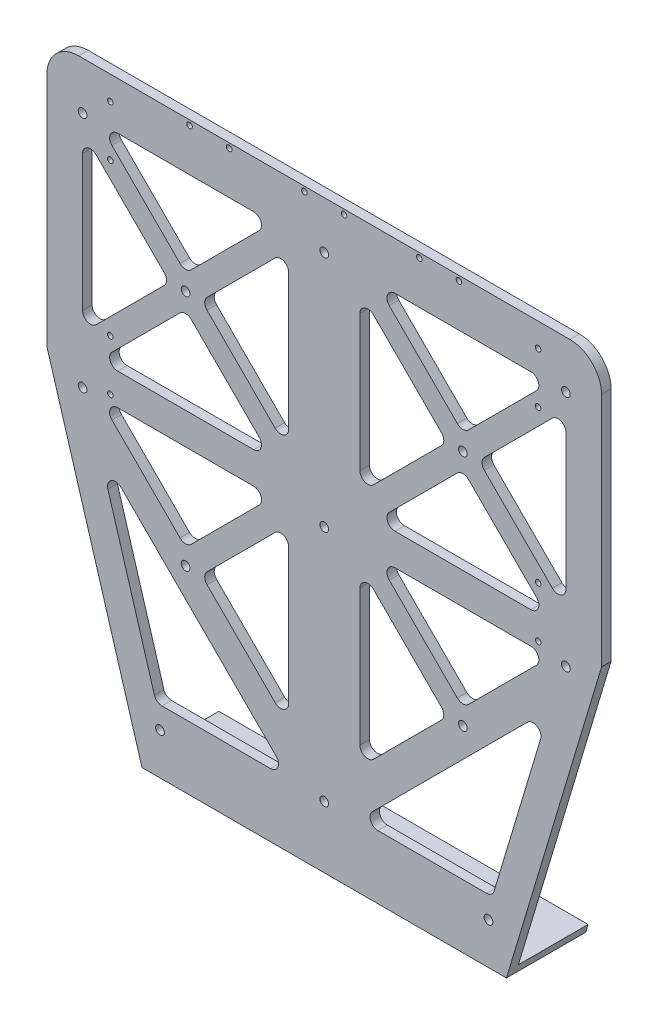
SolidWorks part; units mm, degrees
material "6061 合金"
ref_plane "前视基准面" through (0, 0, 0) normal (0, 0, 1) x (1, 0, 0)
ref_plane "上视基准面" through (0, 0, 0) normal (0, 1, 0) x (1, 0, 0)
ref_plane "右视基准面" through (0, 0, 0) normal (1, 0, 0) x (0, 0, -1)
other "Configuration Table"
sketch "草图1" plane through (0, 0, 0) normal (0, 1, 0) x (1, 0, 0)
  line L0 (0, 55.3951) -> (0, -55.5471) construction
  line L1 (-216.8213, 25) -> (288.5349, 25) construction
  line L2 (-175, 50) -> (175, 50)
  line L3 (-175, 50) -> (-175, 0)
  line L4 (-175, 0) -> (175, 0)
  line L5 (175, 50) -> (175, 0)
  line L6 (10, 25) -> (90, 25) construction
  circle A0 centre (130, 25) radius 2.75
  circle A1 centre (50, 25) radius 2.75
  circle A2 centre (-130, 25) radius 2.75
  circle A3 centre (-50, 25) radius 2.75
  circle A4 centre (10, 25) radius 2.75
  circle A5 centre (90, 25) radius 2.75
  circle A6 centre (-90, 25) radius 2.75
  circle A7 centre (-10, 25) radius 2.75
  dimension "D3" = 5.5
  dimension "D6" = 40
  dimension "D1" = 50
  dimension "D2" = 350
  dimension "D4" = 80
  dimension "D5" = 50
  dimension "D8" = 80
  dimension "D7" = 2
extrude "凸台-拉伸1" add sketch "草图1" along normal blind 5
sketch "草图2" plane through (0, 5, 0) normal (0, 1, 0) x (1, 0, 0)
  line L0 (-175, 50) -> (-175, 0) construction
  line L1 (-175, 6) -> (175, 6)
  line L2 (-175, 6) -> (-175, 0)
  line L3 (-175, 0) -> (175, 0)
  line L4 (175, 6) -> (175, 0)
  dimension "D1" = 6
extrude "凸台-拉伸2" add sketch "草图2" along normal blind 364
sketch "草图3" plane through (0, 0, -6) normal (0, 0, -1) x (-1, 0, 0)
  line L0 (83.9645, 137.5355) -> (41.0355, 180.4645)
  line L1 (0, 0) -> (0, 572.5398) construction
  line L2 (44.5711, 189) -> (130.4289, 189)
  line L15 (133.9645, 180.4645) -> (91.0355, 137.5355)
  line L28 (44.5711, 339) -> (130.4289, 339)
  line L29 (133.9645, 330.4645) -> (91.0355, 287.5355)
  line L30 (83.9645, 287.5355) -> (41.0355, 330.4645)
  line L31 (-175, 369) -> (175, 369) construction
  line L32 (87.5, 645.5729) -> (87.5, -148.8574) construction
  line L33 (73.9645, 120.4645) -> (31.0355, 77.5355)
  line L34 (175, 369) -> (175, 5) construction
  line L35 (101.0355, 277.5355) -> (143.9645, 320.4645)
  line L36 (152.5, 316.9289) -> (152.5, 231.0711)
  line L37 (143.9645, 227.5355) -> (101.0355, 270.4645)
  line L38 (91.0355, 260.4645) -> (133.9645, 217.5355)
  line L39 (130.4289, 209) -> (44.5711, 209)
  line L40 (41.0355, 217.5355) -> (83.9645, 260.4645)
  line L41 (73.9645, 270.4645) -> (31.0355, 227.5355)
  line L42 (22.5, 231.0711) -> (22.5, 316.9289)
  line L43 (31.0355, 320.4645) -> (73.9645, 277.5355)
  line L104 (22.5, 81.0711) -> (22.5, 166.9289)
  line L105 (31.0355, 170.4645) -> (73.9645, 127.5355)
  line L106 (101.0355, 127.5355) -> (143.9645, 170.4645) construction
  line L107 (152.5, 166.9289) -> (152.5, 81.0711) construction
  line L108 (143.9645, 77.5355) -> (101.0355, 120.4645) construction
  line L109 (91.0355, 110.4645) -> (133.9645, 67.5355) construction
  line L110 (130.4289, 59) -> (44.5711, 59) construction
  line L111 (41.0355, 67.5355) -> (83.9645, 110.4645) construction
  line L124 (-91.0355, 137.5355) -> (-133.9645, 180.4645)
  line L125 (-130.4289, 189) -> (-44.5711, 189)
  line L126 (-41.0355, 180.4645) -> (-83.9645, 137.5355)
  line L127 (-101.0355, 120.4645) -> (-143.9645, 77.5355) construction
  line L128 (-152.5, 81.0711) -> (-152.5, 166.9289) construction
  line L129 (-143.9645, 170.4645) -> (-101.0355, 127.5355) construction
  line L130 (-73.9645, 127.5355) -> (-31.0355, 170.4645)
  line L131 (-22.5, 166.9289) -> (-22.5, 81.0711)
  line L132 (-31.0355, 77.5355) -> (-73.9645, 120.4645)
  line L133 (-83.9645, 110.4645) -> (-41.0355, 67.5355) construction
  line L134 (-44.5711, 59) -> (-130.4289, 59) construction
  line L135 (-133.9645, 67.5355) -> (-91.0355, 110.4645) construction
  line L148 (-91.0355, 287.5355) -> (-133.9645, 330.4645)
  line L149 (-130.4289, 339) -> (-44.5711, 339)
  line L150 (-41.0355, 330.4645) -> (-83.9645, 287.5355)
  line L151 (-101.0355, 270.4645) -> (-143.9645, 227.5355)
  line L152 (-152.5, 231.0711) -> (-152.5, 316.9289)
  line L153 (-143.9645, 320.4645) -> (-101.0355, 277.5355)
  line L154 (-73.9645, 277.5355) -> (-31.0355, 320.4645)
  line L155 (-22.5, 316.9289) -> (-22.5, 231.0711)
  line L156 (-31.0355, 227.5355) -> (-73.9645, 270.4645)
  line L157 (-83.9645, 260.4645) -> (-41.0355, 217.5355)
  line L158 (-44.5711, 209) -> (-130.4289, 209)
  line L159 (-133.9645, 217.5355) -> (-91.0355, 260.4645)
  line L160 (83.9645, -12.4645) -> (41.0355, 30.4645) [skipped]
  line L161 (133.9645, 30.4645) -> (91.0355, -12.4645) [skipped]
  line L162 (73.9645, -29.5355) -> (31.0355, -72.4645) [skipped]
  line L163 (22.5, -68.9289) -> (22.5, 16.9289) [skipped]
  line L164 (31.0355, 20.4645) -> (73.9645, -22.4645) [skipped]
  line L165 (101.0355, -22.4645) -> (143.9645, 20.4645) [skipped]
  line L166 (152.5, 16.9289) -> (152.5, -68.9289) [skipped]
  line L167 (143.9645, -72.4645) -> (101.0355, -29.5355) [skipped]
  line L168 (91.0355, -39.5355) -> (133.9645, -82.4645) [skipped]
  line L169 (130.4289, -91) -> (44.5711, -91) [skipped]
  line L170 (41.0355, -82.4645) -> (83.9645, -39.5355) [skipped]
  line L171 (-91.0355, -12.4645) -> (-133.9645, 30.4645) [skipped]
  line L172 (-41.0355, 30.4645) -> (-83.9645, -12.4645) [skipped]
  line L173 (-101.0355, -29.5355) -> (-143.9645, -72.4645) [skipped]
  line L174 (-152.5, -68.9289) -> (-152.5, 16.9289) [skipped]
  line L175 (-143.9645, 20.4645) -> (-101.0355, -22.4645) [skipped]
  line L176 (-73.9645, -22.4645) -> (-31.0355, 20.4645) [skipped]
  line L177 (-22.5, 16.9289) -> (-22.5, -68.9289) [skipped]
  line L178 (-31.0355, -72.4645) -> (-73.9645, -29.5355) [skipped]
  line L179 (-83.9645, -39.5355) -> (-41.0355, -82.4645) [skipped]
  line L180 (-44.5711, -91) -> (-130.4289, -91) [skipped]
  line L181 (-133.9645, -82.4645) -> (-91.0355, -39.5355) [skipped]
  line L182 (44.5711, 39) -> (130.4289, 39) [skipped]
  line L183 (-130.4289, 39) -> (-44.5711, 39) [skipped]
  arc A0 (22.5, 316.9289) -> (31.0355, 320.4645) centre (27.5, 316.9289) cw
  arc A1 (31.0355, 227.5355) -> (22.5, 231.0711) centre (27.5, 231.0711) cw
  arc A2 (73.9645, 270.4645) -> (73.9645, 277.5355) centre (70.4289, 274) ccw
  arc A3 (44.5711, 209) -> (41.0355, 217.5355) centre (44.5711, 214) cw
  arc A4 (130.4289, 209) -> (133.9645, 217.5355) centre (130.4289, 214) ccw
  arc A5 (91.0355, 260.4645) -> (83.9645, 260.4645) centre (87.5, 256.9289) ccw
  arc A6 (101.0355, 270.4645) -> (101.0355, 277.5355) centre (104.5711, 274) cw
  arc A7 (143.9645, 227.5355) -> (152.5, 231.0711) centre (147.5, 231.0711) ccw
  arc A8 (152.5, 316.9289) -> (143.9645, 320.4645) centre (147.5, 316.9289) ccw
  arc A9 (91.0355, 287.5355) -> (83.9645, 287.5355) centre (87.5, 291.0711) cw
  arc A10 (133.9645, 330.4645) -> (130.4289, 339) centre (130.4289, 334) ccw
  arc A11 (41.0355, 330.4645) -> (44.5711, 339) centre (44.5711, 334) cw
  arc A12 (41.0355, 180.4645) -> (44.5711, 189) centre (44.5711, 184) cw
  arc A13 (91.0355, 137.5355) -> (83.9645, 137.5355) centre (87.5, 141.0711) cw
  arc A14 (133.9645, 180.4645) -> (130.4289, 189) centre (130.4289, 184) ccw
  arc A15 (73.9645, 120.4645) -> (73.9645, 127.5355) centre (70.4289, 124) ccw
  arc A16 (31.0355, 77.5355) -> (22.5, 81.0711) centre (27.5, 81.0711) cw
  arc A17 (22.5, 166.9289) -> (31.0355, 170.4645) centre (27.5, 166.9289) cw
  arc A18 (152.5, 166.9289) -> (143.9645, 170.4645) centre (147.5, 166.9289) ccw construction
  arc A19 (101.0355, 120.4645) -> (101.0355, 127.5355) centre (104.5711, 124) cw construction
  arc A20 (143.9645, 77.5355) -> (152.5, 81.0711) centre (147.5, 81.0711) ccw construction
  arc A21 (91.0355, 110.4645) -> (83.9645, 110.4645) centre (87.5, 106.9289) ccw construction
  arc A22 (130.4289, 59) -> (133.9645, 67.5355) centre (130.4289, 64) ccw construction
  arc A23 (44.5711, 59) -> (41.0355, 67.5355) centre (44.5711, 64) cw construction
  arc A36 (-133.9645, 180.4645) -> (-130.4289, 189) centre (-130.4289, 184) cw
  arc A37 (-83.9645, 137.5355) -> (-91.0355, 137.5355) centre (-87.5, 141.0711) cw
  arc A38 (-41.0355, 180.4645) -> (-44.5711, 189) centre (-44.5711, 184) ccw
  arc A39 (-101.0355, 120.4645) -> (-101.0355, 127.5355) centre (-104.5711, 124) ccw construction
  arc A40 (-143.9645, 77.5355) -> (-152.5, 81.0711) centre (-147.5, 81.0711) cw construction
  arc A41 (-152.5, 166.9289) -> (-143.9645, 170.4645) centre (-147.5, 166.9289) cw construction
  arc A42 (-22.5, 166.9289) -> (-31.0355, 170.4645) centre (-27.5, 166.9289) ccw
  arc A43 (-73.9645, 120.4645) -> (-73.9645, 127.5355) centre (-70.4289, 124) cw
  arc A44 (-31.0355, 77.5355) -> (-22.5, 81.0711) centre (-27.5, 81.0711) ccw
  arc A45 (-83.9645, 110.4645) -> (-91.0355, 110.4645) centre (-87.5, 106.9289) ccw construction
  arc A46 (-44.5711, 59) -> (-41.0355, 67.5355) centre (-44.5711, 64) ccw construction
  arc A47 (-130.4289, 59) -> (-133.9645, 67.5355) centre (-130.4289, 64) cw construction
  arc A60 (-133.9645, 330.4645) -> (-130.4289, 339) centre (-130.4289, 334) cw
  arc A61 (-83.9645, 287.5355) -> (-91.0355, 287.5355) centre (-87.5, 291.0711) cw
  arc A62 (-41.0355, 330.4645) -> (-44.5711, 339) centre (-44.5711, 334) ccw
  arc A63 (-101.0355, 270.4645) -> (-101.0355, 277.5355) centre (-104.5711, 274) ccw
  arc A64 (-143.9645, 227.5355) -> (-152.5, 231.0711) centre (-147.5, 231.0711) cw
  arc A65 (-152.5, 316.9289) -> (-143.9645, 320.4645) centre (-147.5, 316.9289) cw
  arc A66 (-22.5, 316.9289) -> (-31.0355, 320.4645) centre (-27.5, 316.9289) ccw
  arc A67 (-73.9645, 270.4645) -> (-73.9645, 277.5355) centre (-70.4289, 274) cw
  arc A68 (-31.0355, 227.5355) -> (-22.5, 231.0711) centre (-27.5, 231.0711) ccw
  arc A69 (-83.9645, 260.4645) -> (-91.0355, 260.4645) centre (-87.5, 256.9289) ccw
  arc A70 (-44.5711, 209) -> (-41.0355, 217.5355) centre (-44.5711, 214) ccw
  arc A71 (-130.4289, 209) -> (-133.9645, 217.5355) centre (-130.4289, 214) cw
  circle A72 centre (87.5, 274) radius 2.75
  circle A73 centre (87.5, 124) radius 2.75
  circle A75 centre (-87.5, 124) radius 2.75
  circle A77 centre (-87.5, 274) radius 2.75
  circle A78 centre (152.5, 339) radius 2.75
  circle A79 centre (152.5, 189) radius 2.75
  circle A80 centre (152.5, 39) radius 2.75
  circle A81 centre (-152.5, 39) radius 2.75
  circle A82 centre (-152.5, 189) radius 2.75
  circle A83 centre (-152.5, 339) radius 2.75
  circle A84 centre (0, 339) radius 2.75
  circle A85 centre (0, 189) radius 2.75
  circle A86 centre (0, 39) radius 2.75
  arc A87 (91.0355, -12.4645) -> (83.9645, -12.4645) centre (87.5, -8.9289) cw [skipped]
  arc A88 (73.9645, -29.5355) -> (73.9645, -22.4645) centre (70.4289, -26) ccw [skipped]
  arc A89 (31.0355, -72.4645) -> (22.5, -68.9289) centre (27.5, -68.9289) cw [skipped]
  arc A90 (22.5, 16.9289) -> (31.0355, 20.4645) centre (27.5, 16.9289) cw [skipped]
  arc A91 (152.5, 16.9289) -> (143.9645, 20.4645) centre (147.5, 16.9289) ccw [skipped]
  arc A92 (101.0355, -29.5355) -> (101.0355, -22.4645) centre (104.5711, -26) cw [skipped]
  arc A93 (143.9645, -72.4645) -> (152.5, -68.9289) centre (147.5, -68.9289) ccw [skipped]
  arc A94 (91.0355, -39.5355) -> (83.9645, -39.5355) centre (87.5, -43.0711) ccw [skipped]
  arc A95 (130.4289, -91) -> (133.9645, -82.4645) centre (130.4289, -86) ccw [skipped]
  arc A96 (44.5711, -91) -> (41.0355, -82.4645) centre (44.5711, -86) cw [skipped]
  arc A97 (-83.9645, -12.4645) -> (-91.0355, -12.4645) centre (-87.5, -8.9289) cw [skipped]
  arc A98 (-101.0355, -29.5355) -> (-101.0355, -22.4645) centre (-104.5711, -26) ccw [skipped]
  arc A99 (-143.9645, -72.4645) -> (-152.5, -68.9289) centre (-147.5, -68.9289) cw [skipped]
  arc A100 (-152.5, 16.9289) -> (-143.9645, 20.4645) centre (-147.5, 16.9289) cw [skipped]
  arc A101 (-22.5, 16.9289) -> (-31.0355, 20.4645) centre (-27.5, 16.9289) ccw [skipped]
  arc A102 (-73.9645, -29.5355) -> (-73.9645, -22.4645) centre (-70.4289, -26) cw [skipped]
  arc A103 (-31.0355, -72.4645) -> (-22.5, -68.9289) centre (-27.5, -68.9289) ccw [skipped]
  arc A104 (-83.9645, -39.5355) -> (-91.0355, -39.5355) centre (-87.5, -43.0711) ccw [skipped]
  arc A105 (-44.5711, -91) -> (-41.0355, -82.4645) centre (-44.5711, -86) ccw [skipped]
  arc A106 (-130.4289, -91) -> (-133.9645, -82.4645) centre (-130.4289, -86) cw [skipped]
  circle A107 centre (87.5, -26) radius 2.75 [skipped]
  circle A108 centre (-87.5, -26) radius 2.75 [skipped]
  arc A109 (133.9645, 30.4645) -> (130.4289, 39) centre (130.4289, 34) ccw [skipped]
  arc A110 (41.0355, 30.4645) -> (44.5711, 39) centre (44.5711, 34) cw [skipped]
  arc A111 (-41.0355, 30.4645) -> (-44.5711, 39) centre (-44.5711, 34) ccw [skipped]
  arc A112 (-133.9645, 30.4645) -> (-130.4289, 39) centre (-130.4289, 34) cw [skipped]
  point P12 (87.5, 274)
  point P25 (87.5, 274)
  point P43 (87.5, 284)
  point P46 (142.5, 339)
  point P49 (32.5, 339)
  dimension "D7" = 5
  dimension "D12" = 5.5
  dimension "D17" = 5.5
  dimension "D20" = 5.5
  dimension "D1" = 45
  dimension "D2" = 45
  dimension "D3" = 110
  dimension "D4" = 30
  dimension "D5" = 10
  dimension "D6" = 4
  dimension "D8" = 3
  dimension "D9" = 2
  dimension "D10" = 20
  dimension "D11" = 45
  dimension "D15" = 150
  dimension "D16" = 175
  dimension "D18" = 3
  dimension "D19" = 150
  dimension "D13" = 3
  dimension "D14" = 2
  dimension "D21" = 3
extrude "切除-拉伸1" cut sketch "草图3" against normal blind 500
sketch "草图4" plane through (0, 0, 0) normal (0, 0, 1) x (1, 0, 0)
  line L0 (0, 0) -> (0, 524.5854) construction
  line L1 (-175, 0) -> (175, 0) construction
  line L2 (-175, 369) -> (175, 369) construction
  circle A0 centre (60, 366) radius 1.75
  circle A1 centre (85, 366) radius 1.75
  circle A2 centre (12.5, 366) radius 1.75
  circle A3 centre (-12.5, 366) radius 1.75
  circle A4 centre (-85, 366) radius 1.75
  circle A5 centre (-60, 366) radius 1.75
  dimension "D1" = 3.5
  dimension "D2" = 3
  dimension "D3" = 60
  dimension "D4" = 25
  dimension "D5" = 12.5
extrude "切除-拉伸2" cut sketch "草图4" against normal blind 10
fillet "圆角1" radius 20 2 edges at (-175, 369, -3) (175, 369, -3)
sketch "草图5" plane through (0, 0, -6) normal (0, 0, -1) x (-1, 0, 0)
  line L0 (0, 431.6761) -> (0, -91.3276) construction
  line L1 (172, 381.63) -> (172, -6.2467) construction
  line L2 (175, 349) -> (175, 5) construction
  line L3 (142.7928, 280) -> (227.4318, 280) construction
  line L4 (-175, 5) -> (175, 5) construction
  line L5 (164.8, 155.6) -> (170, 155.6)
  line L6 (164.8, 155.6) -> (164.8, 130.4)
  line L7 (164.8, 130.4) -> (170, 130.4)
  line L8 (170, 155.6) -> (170, 130.4)
  line L9 (164.8, 110.4) -> (170, 110.4)
  line L10 (164.8, 110.4) -> (164.8, 85.2)
  line L11 (164.8, 85.2) -> (170, 85.2)
  line L12 (170, 110.4) -> (170, 85.2)
  line L13 (164.8, 65.2) -> (170, 65.2)
  line L14 (164.8, 65.2) -> (164.8, 40)
  line L15 (164.8, 40) -> (170, 40)
  line L16 (170, 65.2) -> (170, 40)
  line L17 (-142.7928, 280) -> (-227.4318, 280) construction
  line L18 (-172, 381.63) -> (-172, -6.2467) construction
  line L19 (-170, 65.2) -> (-170, 40)
  line L20 (-164.8, 40) -> (-170, 40)
  line L21 (-164.8, 65.2) -> (-164.8, 40)
  line L22 (-164.8, 65.2) -> (-170, 65.2)
  line L23 (-170, 110.4) -> (-170, 85.2)
  line L24 (-164.8, 85.2) -> (-170, 85.2)
  line L25 (-164.8, 110.4) -> (-164.8, 85.2)
  line L26 (-164.8, 110.4) -> (-170, 110.4)
  line L27 (-170, 155.6) -> (-170, 130.4)
  line L28 (-164.8, 130.4) -> (-170, 130.4)
  line L29 (-164.8, 155.6) -> (-164.8, 130.4)
  line L30 (-164.8, 155.6) -> (-170, 155.6)
  circle A0 centre (172, 330) radius 1.75
  circle A1 centre (172, 230) radius 1.75
  circle A2 centre (-172, 230) radius 1.75
  circle A3 centre (-172, 330) radius 1.75
  dimension "D2" = 3.5
  dimension "D1" = 3
  dimension "D3" = 100
  dimension "D4" = 69
  dimension "D5" = 5.2
  dimension "D6" = 25.2
  dimension "D7" = 25.2
  dimension "D8" = 5.2
  dimension "D9" = 25.2
  dimension "D10" = 20
  dimension "D11" = 20
  dimension "D12" = 35
  dimension "D13" = 5
extrude "切除-拉伸3" [suppressed] cut sketch "草图5" against normal blind 10 contours A0 | A1 | A2 | A3
sketch "草图8" plane through (0, 0, -6) normal (0, 0, -1) x (-1, 0, 0)
  line L0 (-175, 200) -> (-115, 0)
  line L1 (-175, 349) -> (-175, 5) construction
  line L2 (-175, 0) -> (175, 0) construction
  line L3 (-115, 0) -> (-175, 0)
  line L4 (-175, 0) -> (-175, 200)
  line L5 (0, 27.5) -> (0, -27.5) construction
  line L6 (175, 0) -> (175, 200)
  line L7 (115, 0) -> (175, 0)
  line L8 (175, 200) -> (115, 0)
  dimension "D1" = 60
  dimension "D2" = 200
extrude "切除-拉伸4" cut sketch "草图8" against normal through all both and the other way through all
sketch "草图9" plane through (0, 0, 0) normal (0, 0, 1) x (1, 0, 0)
  line L0 (-136.5643, 141.4831) -> (-107.1884, 43.5633)
  line L1 (-102.3992, 40) -> (-33.8553, 40)
  line L2 (-30.3198, 48.5355) -> (-128.2397, 146.4554)
  line L3 (-31.0355, 77.5355) -> (-73.9645, 120.4645) construction
  line L5 (-175, 200) -> (-115, 0) construction
  line L7 (-115, 0) -> (115, 0) construction
  line L8 (0, -27.5) -> (0, 27.5) construction
  line L9 (30.3198, 48.5355) -> (128.2397, 146.4554)
  line L10 (102.3992, 40) -> (33.8553, 40)
  line L11 (136.5643, 141.4831) -> (107.1884, 43.5633)
  arc A0 (-33.8553, 40) -> (-30.3198, 48.5355) centre (-33.8553, 45) ccw
  arc A1 (-107.1884, 43.5633) -> (-102.3992, 40) centre (-102.3992, 45) ccw
  arc A2 (-136.5643, 141.4831) -> (-128.2397, 146.4554) centre (-131.7752, 142.9198) cw
  arc A3 (136.5643, 141.4831) -> (128.2397, 146.4554) centre (131.7752, 142.9198) ccw
  arc A4 (107.1884, 43.5633) -> (102.3992, 40) centre (102.3992, 45) cw
  arc A5 (33.8553, 40) -> (30.3198, 48.5355) centre (33.8553, 45) cw
  dimension "D4" = 5
  dimension "D1" = 20
  dimension "D2" = 20
  dimension "D3" = 40
extrude "切除-拉伸5" cut sketch "草图9" against normal blind 10
sketch "草图10" plane through (0, 0, -6) normal (0, 0, -1) x (-1, 0, 0)
  line L1 (-152.5, 189) -> (-103.6509, 26.1695) construction
  line L2 (-175, 200) -> (-116.5, 5) construction
  line L3 (0, 27.5) -> (0, -27.5) construction
  circle A0 centre (-103.6509, 26.1695) radius 2.75
  circle A1 centre (-152.5, 189) radius 2.75 construction
  circle A2 centre (103.6509, 26.1695) radius 2.75
  dimension "D1" = 170
extrude "切除-拉伸6" cut sketch "草图10" against normal blind 10
sketch "草图11" plane through (0, 0, -6) normal (0, 0, -1) x (-1, 0, 0)
  line L0 (-175, 349) -> (-175, 200) construction
  line L1 (-155, 369) -> (155, 369) construction
  line L2 (0, 27.5) -> (0, -27.5) construction
  circle A0 centre (-135, 354) radius 1.75
  circle A1 centre (-135, 322) radius 1.75
  circle A2 centre (-135, 290) radius 1.75
  circle A3 centre (-135, 258) radius 1.75
  circle A4 centre (-135, 226) radius 1.75
  circle A5 centre (-135, 194) radius 1.75
  circle A6 centre (135, 194) radius 1.75
  circle A7 centre (135, 226) radius 1.75
  circle A8 centre (135, 258) radius 1.75
  circle A9 centre (135, 290) radius 1.75
  circle A10 centre (135, 322) radius 1.75
  circle A11 centre (135, 354) radius 1.75
  dimension "D1" = 40
  dimension "D2" = 3.5
  dimension "D3" = 15
  dimension "D5" = 32
  dimension "D4" = 6
extrude "切除-拉伸7" cut sketch "草图11" against normal blind 10
